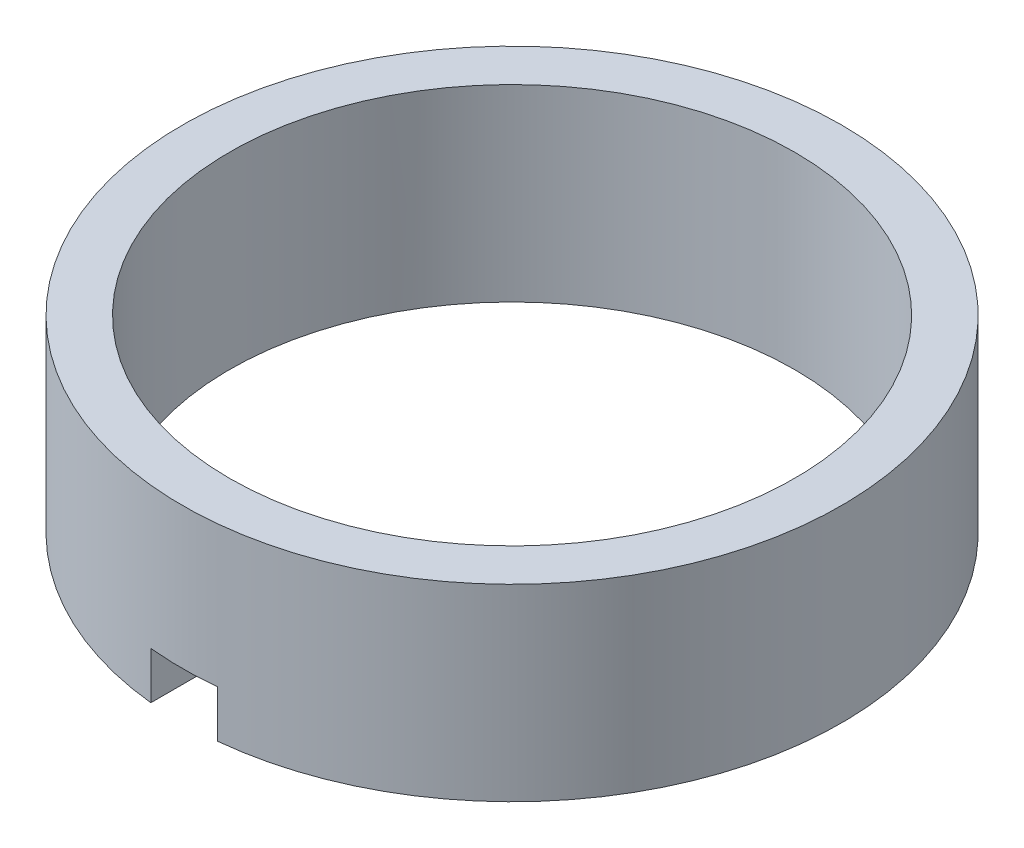
SolidWorks part; units mm, degrees
ref_plane "Front Plane" through (0, 0, 0) normal (1, 0, 0) x (0, 1, 0)
ref_plane "Top Plane" through (0, 0, 0) normal (0, 0, 1) x (0, 1, 0)
ref_plane "Right Plane" through (0, 0, 0) normal (0, 1, 0) x (-1, 0, 0)
sketch "Sketch1" plane through (0, 0, 0) normal (0, 0, 1) x (0, 1, 0)
  line L0 (-38.1, 133.35) -> (38.1, 133.35)
  line L1 (38.1, 133.35) -> (38.1, 114.3254)
  line L2 (38.1, 114.3254) -> (-38.1, 114.3254)
  line L3 (-38.1, 114.3254) -> (-38.1, 133.35)
  line L4 (-63.5, 0) -> (63.5, 0) construction
revolve "Revolve1" add sketch "Sketch1" angle 360 about L4
sketch "Sketch2" plane through (0, 0, 0) normal (0, 1, 0) x (-1, 0, 0)
  line L1 (-13.4874, 0) -> (13.4874, 0)
  line L2 (-13.4874, 0) -> (-13.4874, 266.7)
  line L3 (-13.4874, 266.7) -> (13.4874, 266.7)
  line L4 (13.4874, 0) -> (13.4874, 266.7)
extrude "Cut-Extrude2" cut sketch "Sketch2" along normal blind 19.05 from offset 38.1
